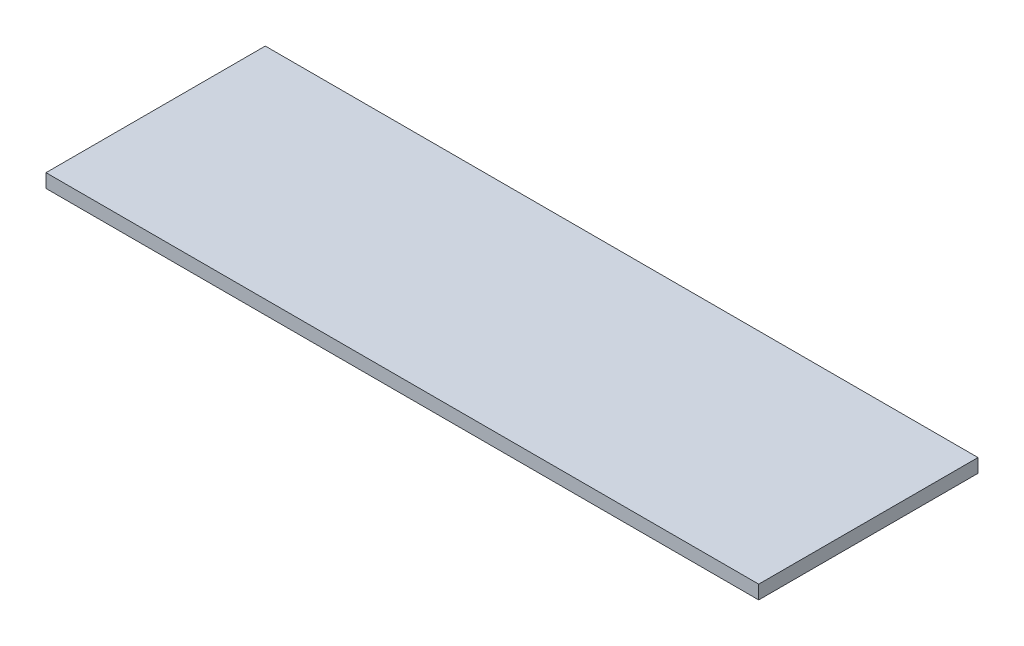
SolidWorks part; units mm, degrees
ref_plane "Front Plane" through (0, 0, 0) normal (0, 0, 1) x (1, 0, 0)
ref_plane "Top Plane" through (0, 0, 0) normal (0, 1, 0) x (1, 0, 0)
ref_plane "Right Plane" through (0, 0, 0) normal (1, 0, 0) x (0, 0, -1)
sketch "Sketch1" plane through (0, 0, 0) normal (0, 1, 0) x (1, 0, 0)
  line L1 (-165.1, 50.8) -> (165.1, 50.8)
  line L2 (-165.1, 50.8) -> (-165.1, -50.8)
  line L3 (-165.1, -50.8) -> (165.1, -50.8)
  line L4 (165.1, 50.8) -> (165.1, -50.8)
  point P4 (0, 50.8)
  point P6 (-165.1, 0)
  dimension "D1" = 330.2
  dimension "D2" = 101.6
extrude "Boss-Extrude1" add sketch "Sketch1" along normal blind 6.35
